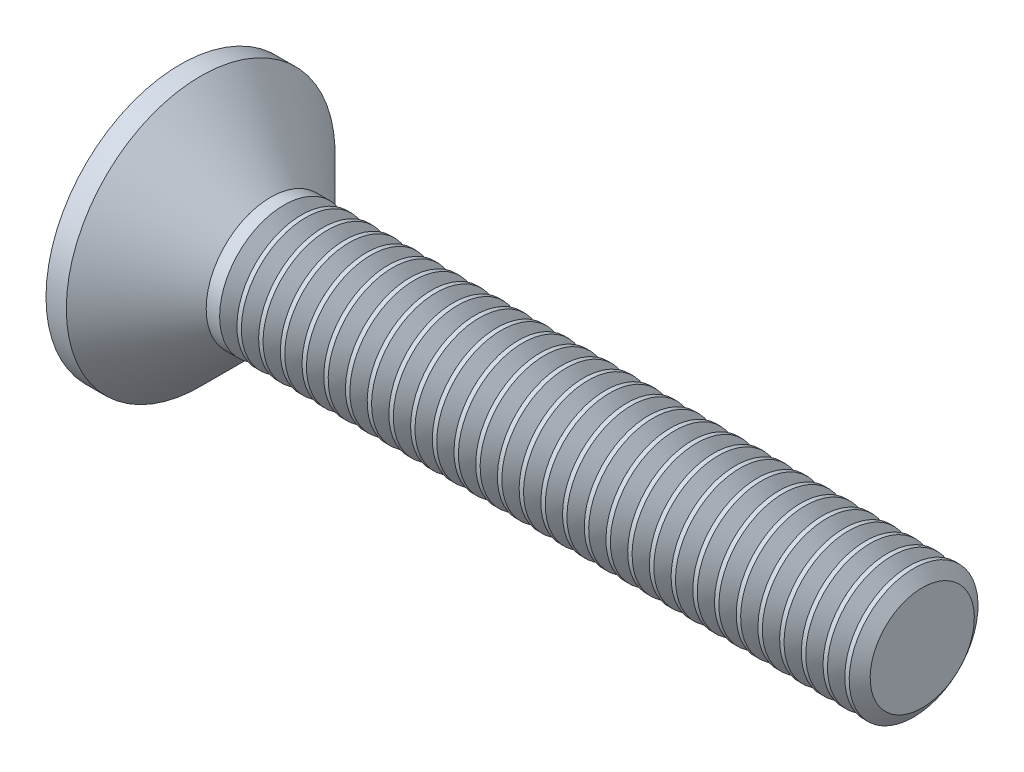
SolidWorks part; units mm, degrees
revolve "Base-Revolve" add sketch "BodySke" angle 360 about L4
sketch "BodySke" plane through (0, 0, 0) normal (0, 0, 1) x (1, 0, 0)
  line L0 (0, 0) -> (20.7803, 0)
  line L1 (20.7803, 0) -> (20.7803, 1.75)
  line L2 (20.7803, 1.75) -> (3.0803, 1.75)
  line L3 (3.0803, 1.75) -> (-6.4176, 11.248) construction
  line L4 (-15.875, 0) -> (82.55, 0) construction
  line L5 (3.0803, -1.75) -> (-6.4176, -11.248) construction
  line L6 (3.6803, 4.925) -> (3.6803, -10.95) construction
  line L7 (0.7803, 8.4875) -> (0.7803, -7.3875) construction
  line L8 (3.0803, 1.75) -> (1.1803, 3.65)
  line L9 (1.1803, 3.65) -> (0.6293, 3.65)
  arc A0 (0, 0) -> (0.6293, 3.65) centre (10.9, 0) cw
  arc A1 (0.7803, 4.05) -> (0, 0) centre (10.9, 0) ccw construction
  dimension "Crown_rad" = 10.9
  dimension "Diameter" = 3.5
  dimension "Advance" = 0.6
  dimension "Thread_nom" = 20
  dimension "Head_ang" = 90
  dimension "D3" = 8.1
  dimension "Side_ht" = 2.3
  dimension "D4" = 0.7803
  dimension "Length" = 20
  dimension "Head_dia" = 7.3
cosmetic thread "ThreadCosmetic" [suppressed] parameters "Thread_length"=17.1, "Thread_minor"=2.829
ref_plane "Plane1" through (0, 0, 0) normal (0, 0, 1) x (1, 0, 0)
ref_plane "Plane2" through (0, 0, 0) normal (0, 1, 0) x (1, 0, 0)
ref_plane "Plane3" through (0, 0, 0) normal (1, 0, 0) x (0, 0, -1)
sketch "Sketch2" plane through (0, 0, 0) normal (1, 0, 0) x (0, 0, -1)
  line L0 (3.65, -0.6) -> (-3.65, -0.6)
  line L1 (3.65, -0.6) -> (3.65, 0.6)
  line L2 (-3.65, 0.6) -> (3.65, 0.6)
  line L3 (-3.65, 0.6) -> (-3.65, -0.6)
  dimension "D1" = 7.3
  dimension "Slot_width" = 1.2
  dimension "D3" = 3.65
  dimension "D4" = 0.6
extrude "Slot" [suppressed] cut sketch "Sketch2" along normal blind 1.7
sketch "Sketch3" plane through (0, 0, 0) normal (1, 0, 0) x (0, 0, -1)
  line L0 (0.47, -2.19) -> (-0.47, -2.19)
  line L1 (0.47, -2.19) -> (0.47, 2.19)
  line L2 (-0.47, 2.19) -> (0.47, 2.19)
  line L3 (-0.47, 2.19) -> (-0.47, -2.19)
  dimension "Cross_width" = 0.94
  dimension "D1" = 0.47
  dimension "Cross_dia" = 4.38
  dimension "D2" = 2.19
ref_plane "Plane4" through (2.48, 0, 0) normal (1, 0, 0) x (0, 0, -1)
sketch "Sketch4" plane through (2.48, 0, 0) normal (1, 0, 0) x (0, 0, -1)
  line L0 (0.235, -0.235) -> (-0.235, -0.235)
  line L1 (0.235, -0.235) -> (0.235, 0.235)
  line L2 (-0.235, 0.235) -> (0.235, 0.235)
  line L3 (-0.235, 0.235) -> (-0.235, -0.235)
  dimension "D1" = 0.47
  dimension "D2" = 0.47
  dimension "D3" = 0.235
  dimension "D4" = 0.235
loft "Cross" cut profiles "Sketch3", "Sketch4"
pattern_circular "CirPattern1" count 2 every 90 about axis through (0, 0, 0) along (1, 0, 0) of "Cross"
sketch "ThdSchSke" plane through (0, 0, 0) normal (0, 0, 1) x (1, 0, 0)
  line L0 (3.6803, -1.4145) -> (3.4454, -1.75)
  line L1 (3.6803, -1.4145) -> (3.9153, -1.75)
  line L2 (3.9153, -1.75) -> (3.9153, -2.1875)
  line L3 (-3.175, 0) -> (5.1513, 0) construction
  line L5 (3.9153, -2.1875) -> (3.4454, -2.1875)
  line L6 (3.4454, -2.1875) -> (3.4454, -1.75)
  line L8 (20.7803, -1.75) -> (20.7803, 1.75) construction
  dimension "Diameter" = 3.5
  dimension "Thread_minor" = 2.829
  dimension "Start" = 17.1
revolve "ThreadSchematic" cut sketch "ThdSchSke" angle 360 about L3
pattern_linear "ThdSchPat" count 30 spacing 0.5897 along (1, 0, 0) of "ThreadSchematic"
equation "\"D1@Sketch2\" = \"Head_dia@BodySke\""
equation "\"D3@Sketch2\" = \"D1@Sketch2\" / 2"
equation "\"D4@Sketch2\" = \"Slot_width@Sketch2\" / 2"
equation "\"D1@Sketch3\" = \"Cross_width@Sketch3\" / 2"
equation "\"D2@Sketch3\" = \"Cross_dia@Sketch3\" / 2"
equation "\"D1@Sketch4\" = \"Cross_width@Sketch3\"*.5"
equation "\"D2@Sketch4\" = \"D1@Sketch4\""
equation "\"D3@Sketch4\" = \"D1@Sketch4\" / 2"
equation "\"D4@Sketch4\" = \"D2@Sketch4\" / 2"
equation "\"Thread_length@ThreadCosmetic\" = ((sgn( (\"Length@BodySke\" - \"Advance@BodySke\" - \"Side_ht@BodySke\" ) - \"Thread_nom@BodySke\" )-1)*( (\"Length@BodySke\" - \"Advance@BodySke\" - \"Side_ht@BodySke\" ) - \"Thread_nom@BodySke\" ))/-2+ \"Thread_nom@BodySke\""
equation "\"Thread_minor@ThdSchSke\" = \"Thread_minor@ThreadCosmetic\""
equation "\"Diameter@ThdSchSke\" = \"Diameter@BodySke\""
equation "\"Overcut@ThdSchSke\" = \"Diameter@BodySke\" * 1.25"
equation "\"Start@ThdSchSke\" =  \"Thread_length@ThreadCosmetic\""
equation "\"Num_threads@ThdSchPat\" = int( \"Thread_length@ThreadCosmetic\" / \"Advance@BodySke\" + 0.999 )  + 1"
equation "\"Advance@ThdSchPat\" = \"Thread_length@ThreadCosmetic\" /  (\"Num_threads@ThdSchPat\" - 1) 'relax it"
